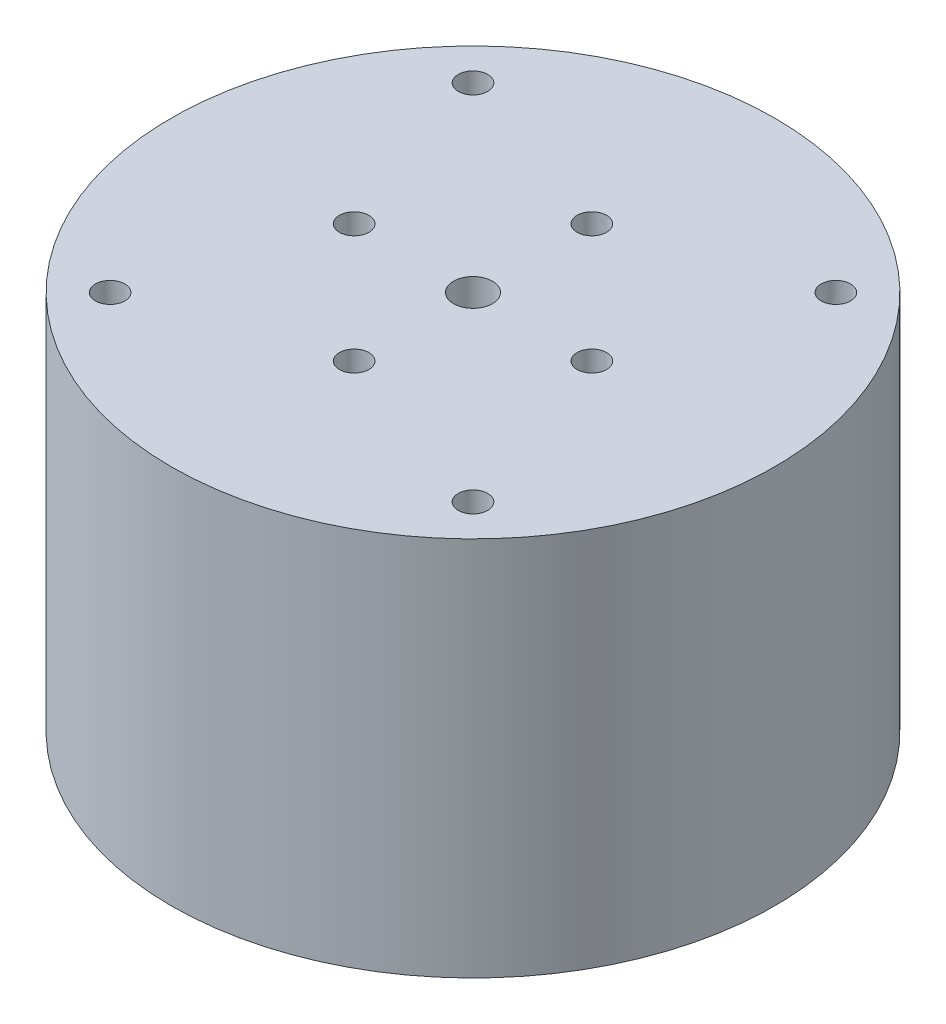
SolidWorks part; units mm, degrees
ref_plane "Front Plane" through (0, 0, 0) normal (0, 0, 1) x (1, 0, 0)
ref_plane "Top Plane" through (0, 0, 0) normal (0, 1, 0) x (1, 0, 0)
ref_plane "Right Plane" through (0, 0, 0) normal (1, 0, 0) x (0, 0, -1)
sketch "Sketch1" plane through (0, 0, 0) normal (0, 1, 0) x (1, 0, 0)
  circle A0 centre (0, 0) radius 31.75
  circle A1 centre (0, 0) radius 2.05
  circle A2 centre (0, 12.5) radius 1.55
  circle A3 centre (12.5, 0) radius 1.55
  circle A4 centre (0, -12.5) radius 1.55
  circle A5 centre (-12.5, 0) radius 1.55
  circle A7 centre (19.083, 19.083) radius 1.55
  circle A9 centre (19.083, -19.083) radius 1.55
  circle A12 centre (-19.083, -19.083) radius 1.55
  circle A14 centre (-19.083, 19.083) radius 1.55
  point P15 (0, 0)
  point P24 (0, 0)
  point P31 (0, 0)
  point P35 (0, 0)
  dimension "D2" = 4
extrude "Boss-Extrude1" add sketch "Sketch1" along normal blind 40
sketch "Sketch2" plane through (0, 0, 0) normal (0, -1, 0) x (1, 0, 0)
  circle A0 centre (0, 0) radius 6.5
extrude "Cut-Extrude1" cut sketch "Sketch2" against normal blind 30
